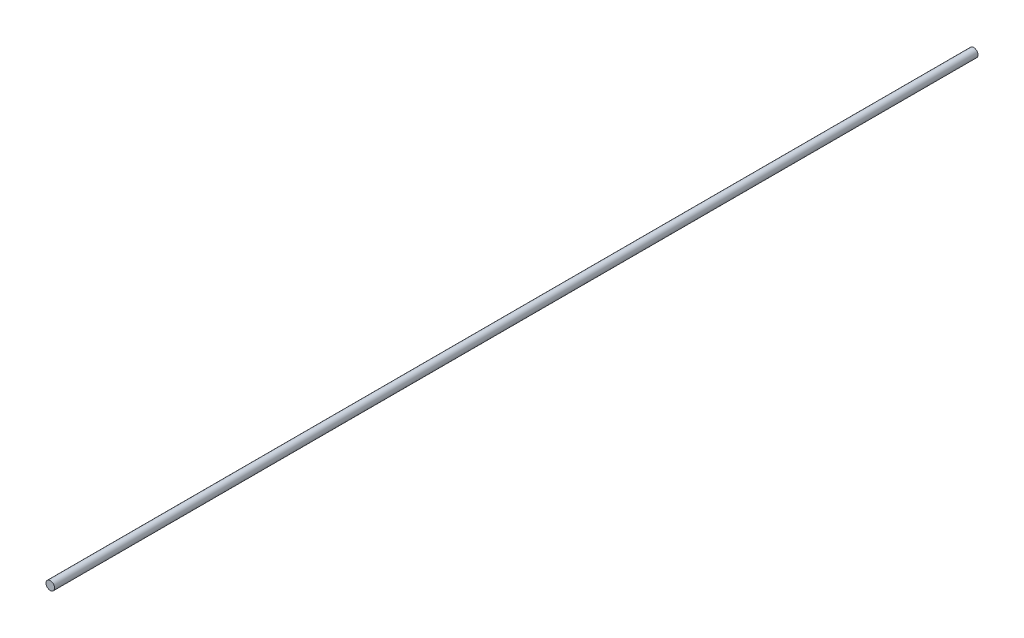
SolidWorks part; units mm, degrees
ref_plane "Front Plane" through (0, 0, 0) normal (0, 0, 1) x (1, 0, 0)
ref_plane "Top Plane" through (0, 0, 0) normal (0, 1, 0) x (1, 0, 0)
ref_plane "Right Plane" through (0, 0, 0) normal (1, 0, 0) x (0, 0, -1)
sketch "Sketch1" plane through (0, 0, 0) normal (0, 0, 1) x (1, 0, 0)
  circle A0 centre (0, 0) radius 1.1811
  dimension "D1" = 2.3622
extrude "Rod" add sketch "Sketch1" along normal blind 254
sketch "Sketch2" plane through (0, 0, 0) normal (0, 1, 0) x (1, 0, 0)
  line L0 (1.1811, -254) -> (1.1811, 0) construction
  line L1 (0.3556, 0) -> (1.1811, 0)
  line L2 (0.3556, 0) -> (0.3556, -7.62)
  line L3 (0.3556, -7.62) -> (1.1811, -7.62)
  line L4 (1.1811, 0) -> (1.1811, -7.62)
  line L6 (-1.1684, 0) -> (-1.9939, 0)
  line L7 (-1.1684, 0) -> (-1.1684, -7.62)
  line L8 (-1.1684, -7.62) -> (-1.9939, -7.62)
  line L9 (-1.9939, 0) -> (-1.9939, -7.62)
  dimension "D1" = 3.175
  dimension "D2" = 1.524
  dimension "D3" = 7.62
extrude "Flats" [suppressed] cut sketch "Sketch2" against normal through all and the other way through all
sketch "Sketch3" plane through (0, 0, 0) normal (1, 0, 0) x (0, 0, -1)
  circle A0 centre (-2.54, 0) radius 0.762
  dimension "D1" = 1.524
  dimension "D2" = 2.54
extrude "Hole" [suppressed] cut sketch "Sketch3" against normal up to next and the other way up to next
